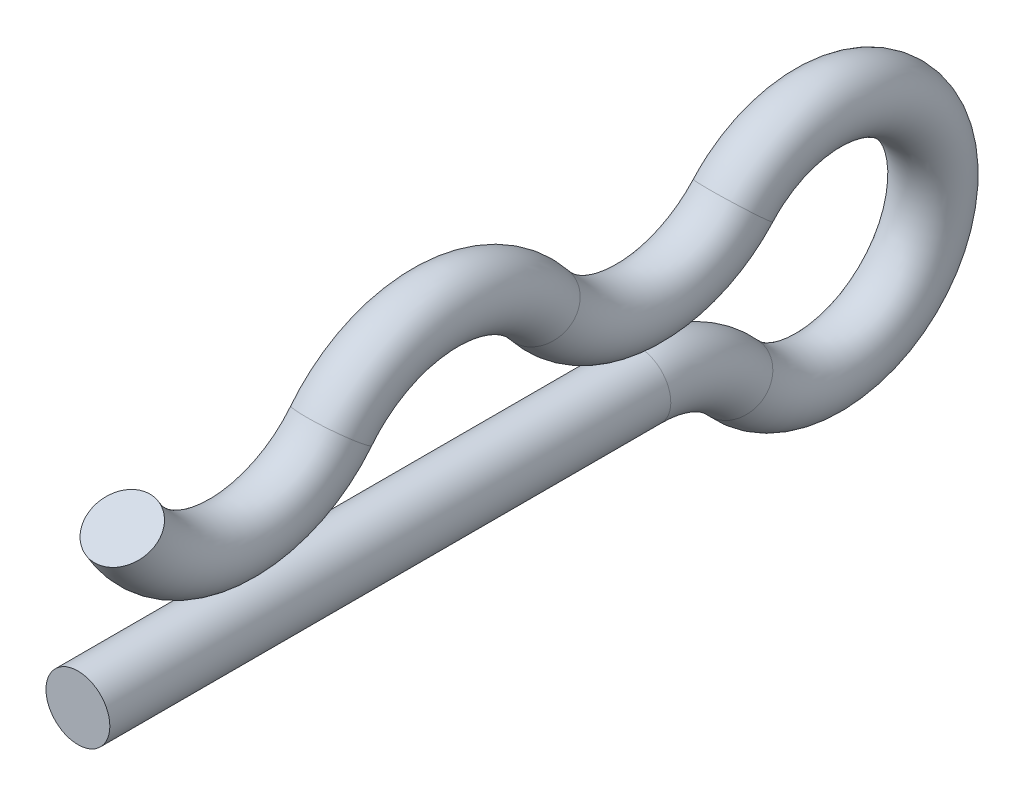
SolidWorks part; units mm, degrees
ref_plane "Front" through (0, 0, 0) normal (0, 0, 1) x (1, 0, 0)
ref_plane "Top" through (0, 0, 0) normal (0, 1, 0) x (1, 0, 0)
ref_plane "Right" through (0, 0, 0) normal (1, 0, 0) x (0, 0, -1)
sketch "Sketch1" plane through (0, 0, 0) normal (1, 0, 0) x (0, 0, -1)
  line L1 (-12.59, 0.7493) -> (-12.59, -0.7493) construction
  line L3 (-3.8529, -0.7493) -> (-15.9004, -0.7493) construction
  line L4 (-15.9004, -0.7493) -> (-15.9004, 0.6223) construction
  line L5 (2.4638, 0) -> (3.1496, 0) construction
  line L14 (-15.9004, 0.6223) -> (-15.7734, 0.6223) construction
  line L15 (-19.6212, 10.205) -> (-22.5342, 15.2504) construction
  circle A0 centre (0, 0) radius 1.778 construction
  circle A2 centre (0, 0) radius 2.4638 construction
  arc A10 (-5.9844, 1.7779) -> (-1.8303, 1.6493) centre (-3.8529, 3.472) ccw construction
  arc A14 (-1.8303, -1.6493) -> (-3.8529, -0.7493) centre (-3.8529, -3.472) ccw construction
  arc A16 (-14.9479, 2.1107) -> (-10.4585, 1.7779) centre (-12.59, 3.472) ccw construction
  arc A17 (-5.9844, 1.7779) -> (-10.4585, 1.7779) centre (-8.2214, 0) ccw construction
  point P4 (0, 2.4638)
  point P6 (0, 0)
  point P11 (-12.59, 0)
  point P16 (-12.59, 0.7493)
  point P23 (-3.8529, 0.7493)
  point P48 (0, 0)
  dimension "EyeID" = 3.556
  dimension "D3" = 2.8575
  dimension "D2" = 0.6858
  dimension "D1" = 0.6858
  dimension "Length" = 19.05
  dimension "Wire OD" = 1.3716
  dimension "Gap" = 0.127
  dimension "D4" = 1.4986
  dimension "D5" = 0.9525
  dimension "D7" = 60
ref_plane "Plane1" through (0, 0, 15.9004) normal (0, 0, 1) x (1, 0, 0)
sketch "Sketch2" plane through (0, 0, 15.9004) normal (0, 0, 1) x (1, 0, 0)
  circle A1 centre (0, -0.7493) radius 0.6858
  dimension "D1" = 1.3716
sketch "Sketch3" plane through (0, 0, 0) normal (1, 0, 0) x (0, 0, -1)
  line L13 (-3.8529, -0.7493) -> (-15.9004, -0.7493) construction
  line L16 (-3.8529, -0.7493) -> (-15.9004, -0.7493)
  arc A12 (-1.8303, -1.6493) -> (-3.8529, -0.7493) centre (-3.8529, -3.472) ccw construction
  circle A15 centre (0, 0) radius 2.4638 construction
  arc A16 (-5.9844, 1.7779) -> (-1.8303, 1.6493) centre (-3.8529, 3.472) ccw construction
  arc A17 (-5.9844, 1.7779) -> (-10.4585, 1.7779) centre (-8.2214, 0) ccw construction
  arc A18 (-14.9479, 2.1107) -> (-10.4585, 1.7779) centre (-12.59, 3.472) ccw construction
  arc A19 (-1.8303, -1.6493) -> (-3.8529, -0.7493) centre (-3.8529, -3.472) ccw
  arc A20 (-1.8303, -1.6493) -> (-1.8303, 1.6493) centre (0, 0) ccw
  arc A21 (-5.9844, 1.7779) -> (-1.8303, 1.6493) centre (-3.8529, 3.472) ccw
  arc A22 (-5.9844, 1.7779) -> (-10.4585, 1.7779) centre (-8.2214, 0) ccw
  arc A23 (-14.9479, 2.1107) -> (-10.4585, 1.7779) centre (-12.59, 3.472) ccw
sweep "Sweep1" add profiles "Sketch2" path "Sketch3"
sketch "Sketch4" plane through (0, 0, 0) normal (1, 0, 0) x (0, 0, -1)
  line L0 (0, -12.7) -> (0, 12.7) construction
  point P4 (0, 0)
  dimension "D1" = 25.4
equation "\"D2@Sketch1\"=\"Wire OD@Sketch1\"/2"
equation "\"D1@Sketch2\"=\"Wire OD@Sketch1\""
equation "\"D1@Sketch1\"=\"Wire OD@Sketch1\"/2"
equation "\"D4@Sketch1\"=\"Gap@Sketch1\"+\"Wire OD@Sketch1\""
equation "\"D5@Sketch1\"=\"Length@Sketch1\"*.05"
equation "\"D3@Sketch1\"=\"Length@Sketch1\"*.15"
